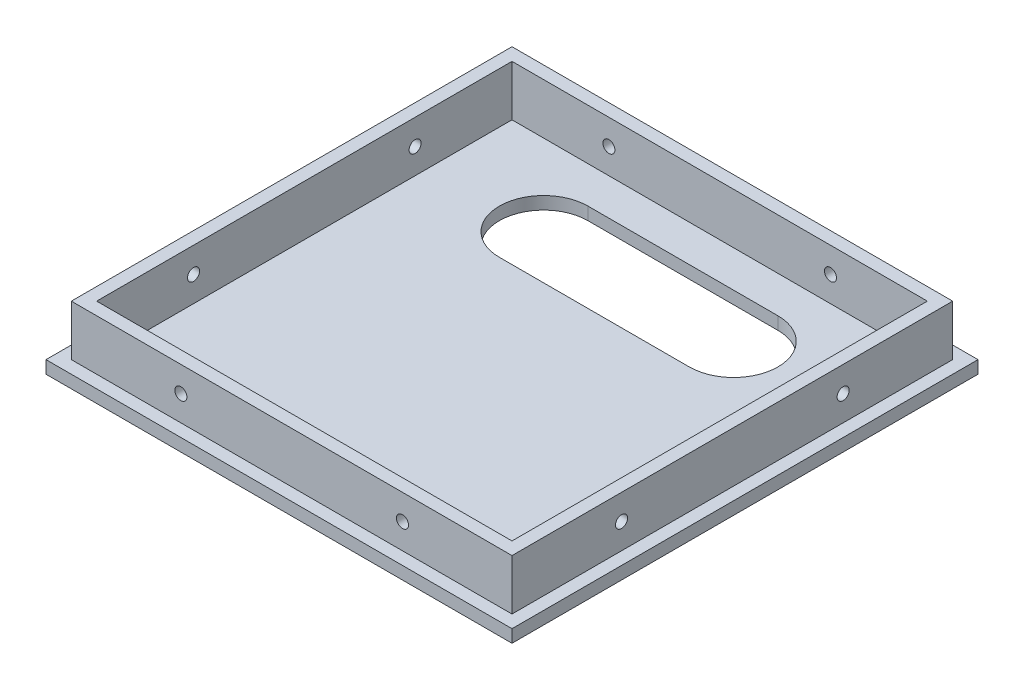
SolidWorks part; units mm, degrees
ref_plane "前视基准面" through (0, 0, 0) normal (0, 0, 1) x (1, 0, 0)
ref_plane "上视基准面" through (0, 0, 0) normal (0, 1, 0) x (1, 0, 0)
ref_plane "右视基准面" through (0, 0, 0) normal (1, 0, 0) x (0, 0, -1)
other "Configuration Table"
sketch "草图1" plane through (0, 0, 0) normal (0, 1, 0) x (1, 0, 0)
  line L0 (-32.8, 32.8) -> (32.8, 32.8)
  line L1 (-34.8, 34.8) -> (34.8, 34.8)
  line L2 (-34.8, 34.8) -> (-34.8, -34.8)
  line L3 (-34.8, -34.8) -> (34.8, -34.8)
  line L4 (34.8, 34.8) -> (34.8, -34.8)
  line L5 (-34.8, 34.8) -> (34.8, -34.8) construction
  line L6 (-34.8, -34.8) -> (34.8, 34.8) construction
  line L7 (32.8, 32.8) -> (32.8, -32.8)
  line L8 (-32.8, -32.8) -> (32.8, -32.8)
  line L9 (-32.8, 32.8) -> (-32.8, -32.8)
  point P0 (0, 0)
  dimension "D1" = 69.6
  dimension "D2" = 69.6
  dimension "D3" = 2
extrude "凸台-拉伸1" add sketch "草图1" along normal blind 8
sketch "草图2" plane through (0, 0, 0) normal (0, -1, 0) x (1, 0, 0)
  line L0 (36.8, 36.8) -> (-36.8, 36.8)
  line L1 (-36.8, 36.8) -> (-36.8, -36.8)
  line L2 (-36.8, -36.8) -> (36.8, -36.8)
  line L3 (36.8, -36.8) -> (36.8, 36.8)
  line L5 (-15, -20) -> (15, -20) construction
  line L6 (-15, -13) -> (15, -13)
  line L12 (-15, -27) -> (15, -27)
  line L13 (0, -42.0732) -> (0, 47.6586) construction
  arc A0 (-15, -13) -> (-15, -27) centre (-15, -20) ccw
  arc A1 (15, -27) -> (15, -13) centre (15, -20) ccw
  point P0 (0, 36.8)
  point P1 (36.8, 0)
  point P9 (0, -20)
  dimension "D4" = 7
  dimension "D1" = 73.6
  dimension "D2" = 73.6
  dimension "D3" = 30
  dimension "D5" = 20
extrude "凸台-拉伸2" add sketch "草图2" along normal blind 2
sketch "草图3" plane through (-34.8, 0, 0) normal (-1, 0, 0) x (0, 0, 1)
  line L0 (0, 29.1396) -> (0, -17.9968) construction
  line L1 (36.8, 0) -> (-36.8, 0) construction
  circle A0 centre (17.5, 4) radius 0.95
  circle A1 centre (-17.5, 4) radius 0.95
  dimension "D1" = 1.9
  dimension "D2" = 35
  dimension "D3" = 4
extrude "切除-拉伸1" cut sketch "草图3" against normal through all
sketch "草图4" plane through (0, 0, -34.8) normal (0, 0, -1) x (-1, 0, 0)
  line L0 (0, 12.0889) -> (0, -5.7935) construction
  line L1 (-34.8, 0) -> (34.8, 0) construction
  circle A0 centre (17.5, 4) radius 0.95
  circle A1 centre (-17.5, 4) radius 0.95
  dimension "D1" = 1.9
  dimension "D2" = 35
  dimension "D3" = 4
extrude "切除-拉伸2" cut sketch "草图4" against normal through all
